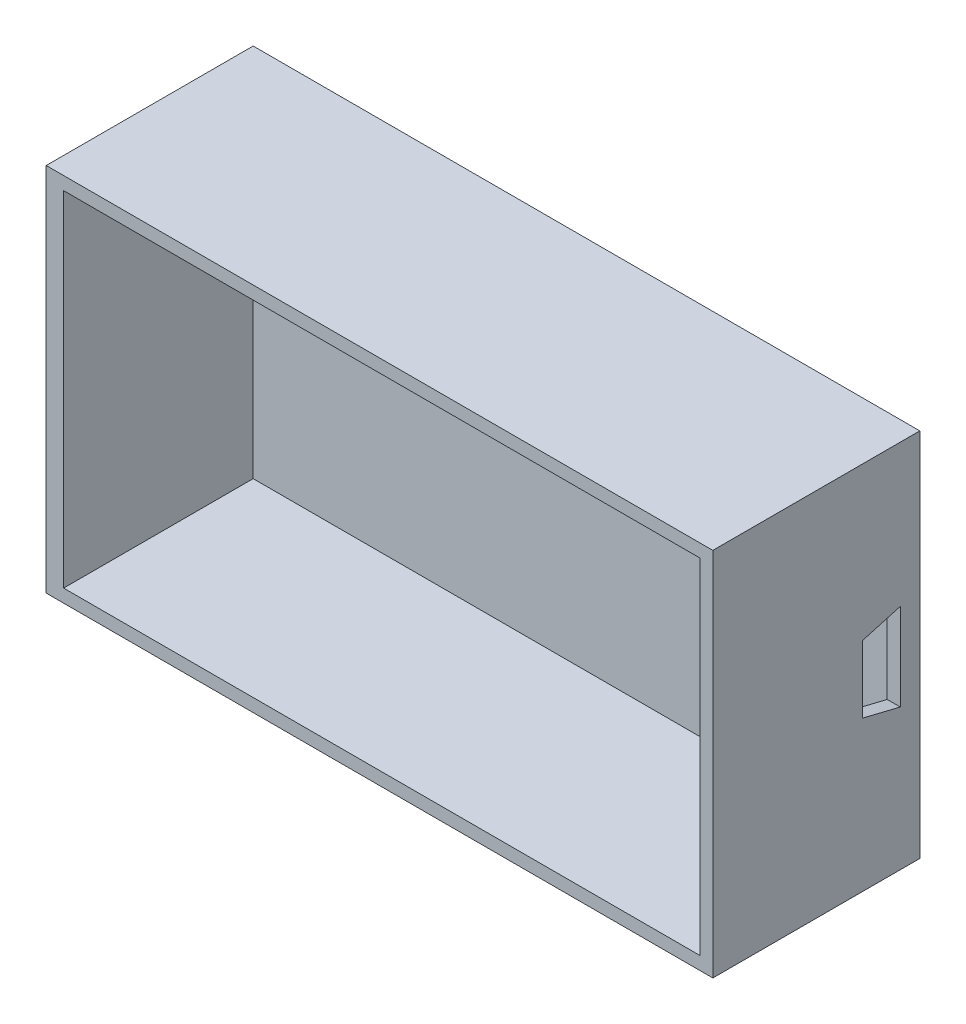
SolidWorks part; units mm, degrees
ref_plane "Ön Düzlem" through (0, 0, 0) normal (0, 0, 1) x (1, 0, 0)
ref_plane "Üst Düzlem" through (0, 0, 0) normal (0, 1, 0) x (1, 0, 0)
ref_plane "Sağ Düzlem" through (0, 0, 0) normal (1, 0, 0) x (0, 0, -1)
sketch "Çizim1" plane through (0, 0, 0) normal (0, 0, 1) x (1, 0, 0)
  line L0 (0, 0) -> (0, 31.6)
  line L1 (0, 31.6) -> (58.4, 31.6)
  line L2 (58.4, 31.6) -> (58.4, 0)
  line L3 (58.4, 0) -> (0, 0)
  line L5 (0, 32.8) -> (59.6, 32.8)
  line L6 (59.6, 32.8) -> (59.6, -1.2)
  line L7 (59.6, -1.2) -> (-1.6, -1.2)
  line L8 (-1.6, -1.2) -> (-1.6, 32.8)
  line L9 (-1.6, 32.8) -> (0, 32.8)
extrude "Yükseklik-Ekstrüzyon1" add sketch "Çizim1" along normal blind 19
sketch "Çizim2" plane through (0, 0, 0) normal (0, 0, 1) x (1, 0, 0)
  line L0 (0, 31.6) -> (58.4, 31.6)
  line L1 (58.4, 31.6) -> (58.4, 0)
  line L2 (58.4, 0) -> (0, 0)
  line L3 (0, 0) -> (0, 31.6)
extrude "Yükseklik-Ekstrüzyon2" add sketch "Çizim2" along normal blind 1.6
sketch "Çizim3" plane through (0, 0, 0) normal (1, 0, 0) x (0, 0, -1)
  line L3 (-1.7901, 19.742) -> (-1.7901, 11.742)
  line L5 (-5.2789, 12.5942) -> (-5.2789, 18.7544)
  line L7 (-1.7901, 19.742) -> (-5.2789, 18.7544)
  line L9 (-5.2789, 12.5942) -> (-1.7901, 11.742)
extrude "Kes-Ekstrüzyon2" cut sketch "Çizim3" against normal blind 3 from surface at 59.6 starting at face at (59.6, 15.8, 9.5)
